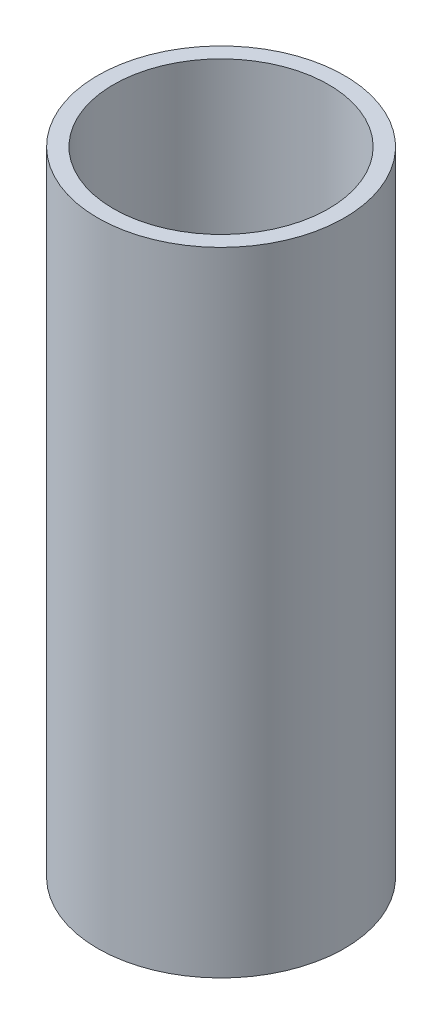
SolidWorks part; units mm, degrees
ref_plane "Front Plane" through (0, 0, 0) normal (0, 0, 1) x (1, 0, 0)
ref_plane "Top Plane" through (0, 0, 0) normal (0, 1, 0) x (1, 0, 0)
ref_plane "Right Plane" through (0, 0, 0) normal (1, 0, 0) x (0, 0, -1)
sketch "Sketch1" plane through (0, 0, 0) normal (0, 1, 0) x (1, 0, 0)
  circle A0 centre (0, 0) radius 5.1
  circle A1 centre (0, 0) radius 5.85
extrude "Boss-Extrude1" add sketch "Sketch1" along normal blind 30
